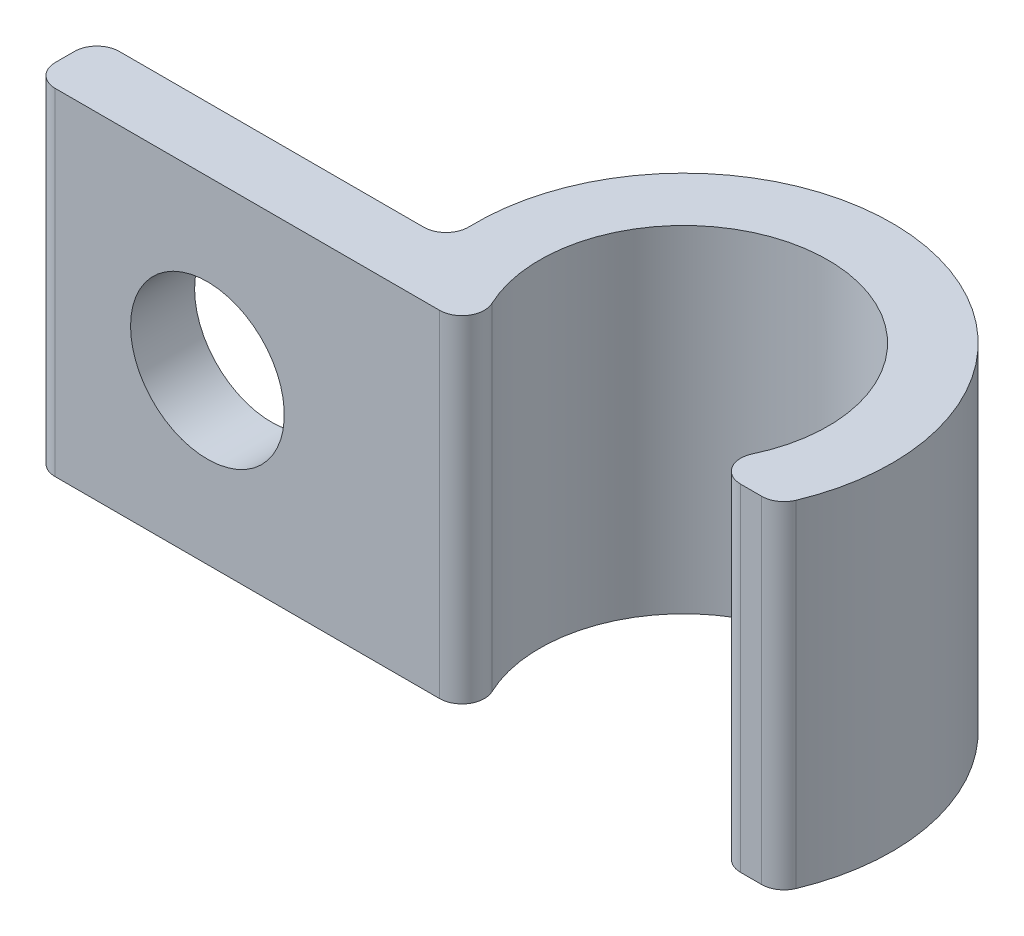
SolidWorks part; units mm, degrees
ref_plane "Plan de face" through (0, 0, 0) normal (0, 0, 1) x (1, 0, 0)
ref_plane "Plan de dessus" through (0, 0, 0) normal (0, 1, 0) x (1, 0, 0)
ref_plane "Plan de droite" through (0, 0, 0) normal (1, 0, 0) x (0, 0, -1)
sketch "Esquisse1" plane through (0, 0, 0) normal (0, 1, 0) x (1, 0, 0)
  line L0 (0, 0) -> (12, 0)
  line L1 (21.4, 0) -> (22.0563, 0)
  line L2 (9.5035, 2) -> (0, 2)
  line L3 (-0.7, 1.3) -> (-0.7, 0.7)
  arc A0 (12, 0) -> (12.6327, 0.9995) centre (12, 0.7) ccw
  arc A1 (12.6327, 0.9995) -> (20.7673, 0.9995) centre (16.7, 2.9249) cw
  arc A2 (20.7673, 0.9995) -> (21.4, 0) centre (21.4, 0.7) ccw
  arc A3 (22.0563, 0) -> (22.7028, 0.4315) centre (22.0563, 0.7) ccw
  arc A4 (22.7028, 0.4315) -> (10.2032, 2.7219) centre (16.7, 2.9249) ccw
  arc A5 (10.2032, 2.7219) -> (9.5035, 2) centre (9.5035, 2.7) cw
  arc A6 (0, 2) -> (-0.7, 1.3) centre (0, 1.3) ccw
  arc A7 (-0.7, 0.7) -> (0, 0) centre (0, 0.7) ccw
  point P0 (19.7584, 1.1202)
  point P5 (6.4344, 14.8167)
  point P22 (0, 0)
  point P23 (19.72, 13.7426)
  point P24 (12, 0)
  point P25 (0, 0)
  dimension "D2" = 0.7
  dimension "D3" = 4.5
  dimension "D4" = 6.5
  dimension "D1" = 12
  dimension "D5" = 2
  dimension "D6" = 9.4
extrude "Boss.-Extru.1" add sketch "Esquisse1" along normal blind 10.5
hole_wizard "Dégagement M41" positions "Esquisse2" profile "Esquisse3" hole size "M4" standard "DIN" end condition through all
sketch "Esquisse2" plane through (0, 0, -2) normal (0, 0, -1) x (-1, 0, 0)
  line L0 (-9.5035, 5.25) -> (0, 5.25) construction
  line L1 (-9.5035, 10.5) -> (-9.5035, 0) construction
  line L2 (0, 10.5) -> (0, 0) construction
  point P0 (-4.7518, 5.25)
  point P10 (0, 0)
sketch "Esquisse3" plane through (4.7518, 5.25, -2) normal (1, 0, 0) x (0, 1, 0)
  line L0 (0, 0) -> (0, 2)
  line L1 (0, 2) -> (2.4, 2)
  line L2 (2.4, 2) -> (2.4, 0)
  line L5 (2.4, 0) -> (0, 0)
  line L11 (0, -6.35) -> (0, 107.95) construction
  dimension "Diamètre du perçage jusqu'au prochain" = 4.8
  dimension "Profondeur du perçage jusqu'au prochain" = 2
equation "\"e\"= 2mm"
equation "\"r\"= 0.7mm"
equation "\"D2@Esquisse1\"=\"r\""
equation "\"rcable\" = 3.5"
equation "\"D3@Esquisse1\"=\"rcable\"+1"
equation "\"D4@Esquisse1\"=\"rcable\"+\"e\"+1"
equation "\"D6@Esquisse1\"=\"rcable\"*2+\"r\"*2+1"
equation "\"D1@Boss.-Extru.1\"=\"rcable\"*3"
